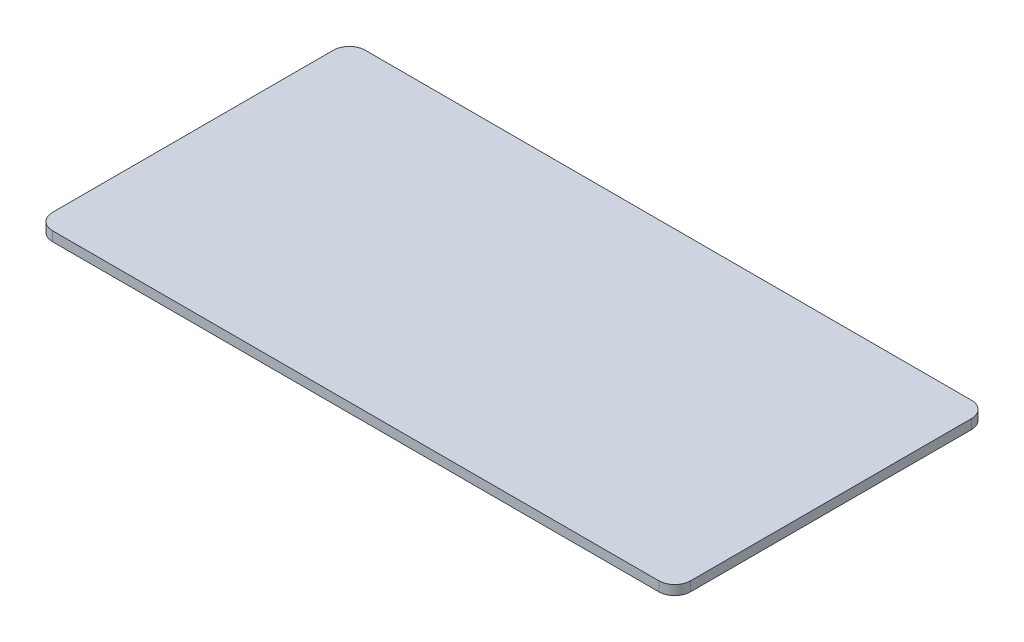
SolidWorks part; units mm, degrees
ref_plane "Front Plane" through (0, 0, 0) normal (0, 0, 1) x (1, 0, 0)
ref_plane "Top Plane" through (0, 0, 0) normal (0, 1, 0) x (1, 0, 0)
ref_plane "Right Plane" through (0, 0, 0) normal (1, 0, 0) x (0, 0, -1)
sketch "Sketch1" plane through (0, 0, 0) normal (0, 1, 0) x (1, 0, 0)
  line L1 (44.4505, -18.1465) -> (-145.5495, -18.1465)
  line L2 (49.4505, -13.1465) -> (49.4505, 74.8535)
  line L3 (44.4505, 79.8535) -> (-145.5495, 79.8535)
  line L4 (-150.5495, -13.1465) -> (-150.5495, 74.8535)
  arc A0 (49.4505, 74.8535) -> (44.4505, 79.8535) centre (44.4505, 74.8535) ccw
  arc A1 (44.4505, -18.1465) -> (49.4505, -13.1465) centre (44.4505, -13.1465) ccw
  arc A2 (-145.5495, -18.1465) -> (-150.5495, -13.1465) centre (-145.5495, -13.1465) cw
  arc A3 (-145.5495, 79.8535) -> (-150.5495, 74.8535) centre (-145.5495, 74.8535) ccw
  point P6 (49.4505, 79.8535)
  point P11 (-150.5495, -18.1465)
  point P14 (-150.5495, 79.8535)
  dimension "D3" = 5
  dimension "D1" = 200
  dimension "D2" = 98
extrude "Boss-Extrude1" add sketch "Sketch1" along normal blind 3
